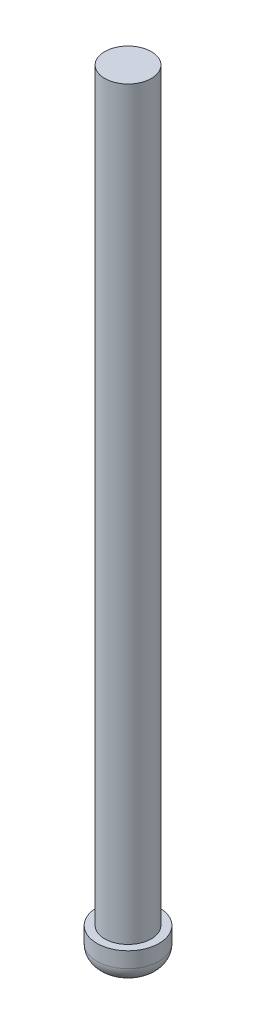
SolidWorks part; units mm, degrees
ref_plane "Alzado" through (0, 0, 0) normal (0, 0, 1) x (1, 0, 0)
ref_plane "Planta" through (0, 0, 0) normal (0, 1, 0) x (1, 0, 0)
ref_plane "Vista lateral" through (0, 0, 0) normal (1, 0, 0) x (0, 0, -1)
sketch "Croquis1" plane through (0, 0, 0) normal (0, 1, 0) x (1, 0, 0)
  circle A0 centre (0, 0) radius 0.75
  dimension "D1" = 1.5
extrude "Saliente-Extruir1" add sketch "Croquis1" along normal blind 24
sketch "Croquis2" plane through (0, 0, 0) normal (0, -1, 0) x (1, 0, 0)
  circle A0 centre (0, 0) radius 1
extrude "Saliente-Extruir2" add sketch "Croquis2" along normal blind 1
fillet "Redondeo1" radius 0.5 1 edges at (0, -1, -1)
